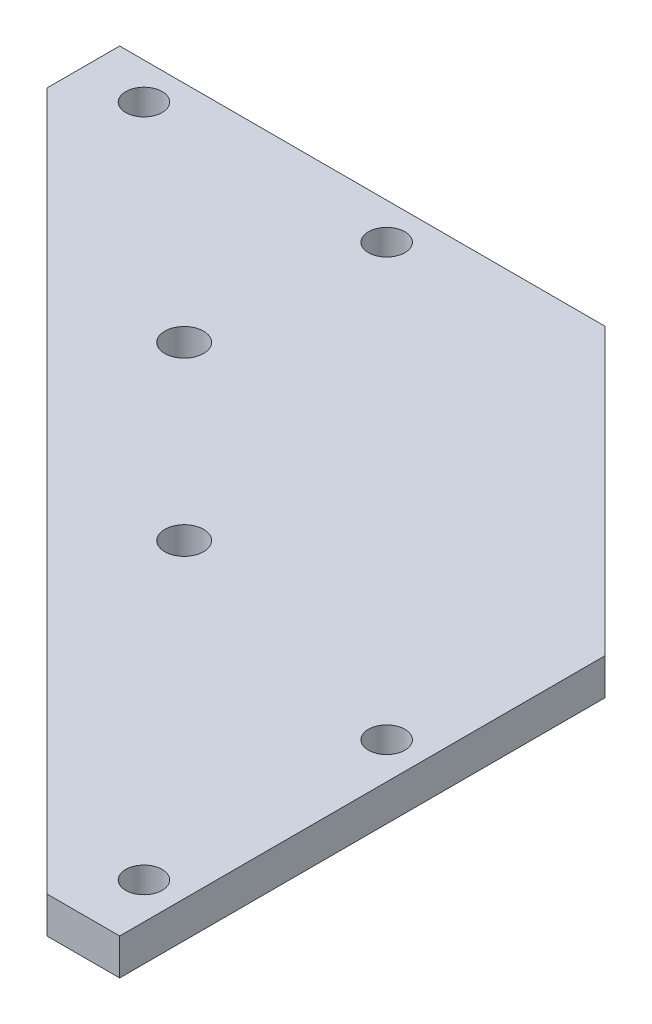
SolidWorks part; units mm, degrees
ref_plane "前视基准面" through (0, 0, 0) normal (0, 0, 1) x (1, 0, 0)
ref_plane "上视基准面" through (0, 0, 0) normal (0, 1, 0) x (1, 0, 0)
ref_plane "右视基准面" through (0, 0, 0) normal (1, 0, 0) x (0, 0, -1)
other "Configuration Table"
sketch "草图1" plane through (0, 0, 0) normal (0, 1, 0) x (1, 0, 0)
  line L0 (0, 0) -> (-40, 0)
  line L1 (-40, 0) -> (-40, -6)
  line L2 (-40, -6) -> (17.5, -63.5)
  line L3 (-11.25, -34.75) -> (11.75, -11.75) construction
  line L4 (23.5, -23.5) -> (0, 0)
  line L5 (23.5, -63.5) -> (17.5, -63.5)
  line L6 (23.5, -23.5) -> (23.5, -63.5)
  line L7 (-35, -3) -> (-40, -3) construction
  line L8 (-35, -3) -> (-15, -3) construction
  circle A0 centre (-35, -3) radius 1.5
  circle A1 centre (-15, -3) radius 1.5
  circle A2 centre (20.5, -58.5) radius 1.5
  circle A3 centre (20.5, -38.5) radius 1.5
  dimension "D6" = 5
  dimension "D7" = 3
  dimension "D1" = 6
  dimension "D2" = 40
  dimension "D3" = 63.5
  dimension "D5" = 20
  dimension "D4" = 2
extrude "凸台-拉伸1" add sketch "草图1" along normal blind 3
sketch "草图2" plane through (0, 3, 0) normal (0, 1, 0) x (1, 0, 0)
  line L0 (-21.8566, -17.0723) -> (6.4277, -45.3566) construction
  line L5 (6.4277, -45.3566) -> (10.6703, -41.114) construction
  line L6 (10.6703, -41.114) -> (-17.614, -12.8297) construction
  line L7 (-17.614, -12.8297) -> (-21.8566, -17.0723) construction
  line L8 (-40, -6) -> (17.5, -63.5) construction
  line L9 (-7.7145, -31.2145) -> (-11.25, -34.75) construction
  line L10 (-19.7353, -14.951) -> (8.549, -43.2353) construction
  circle A0 centre (-16.1997, -18.4865) radius 1.6
  circle A1 centre (-2.0576, -32.6287) radius 1.6
  dimension "D6" = 3.2
  dimension "D1" = 5
  dimension "D2" = 6
  dimension "D3" = 40
  dimension "D4" = 5
  dimension "D5" = 20
extrude "切除-拉伸1" cut sketch "草图2" against normal blind 10
